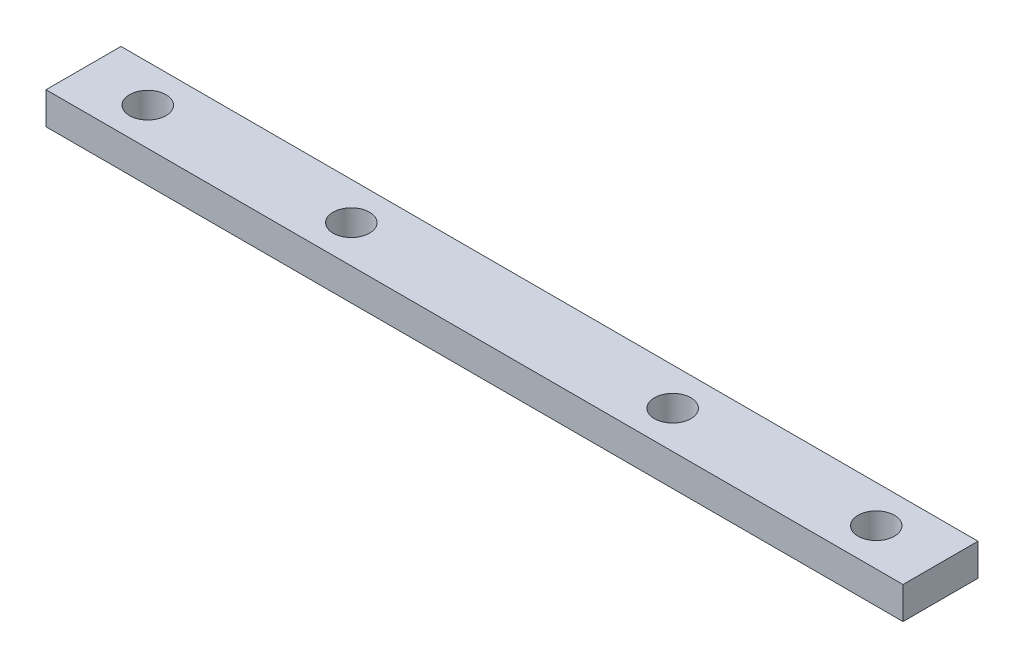
SolidWorks part; units mm, degrees
ref_plane "Front Plane" through (0, 0, 0) normal (0, 0, 1) x (1, 0, 0)
ref_plane "Top Plane" through (0, 0, 0) normal (0, 1, 0) x (1, 0, 0)
ref_plane "Right Plane" through (0, 0, 0) normal (1, 0, 0) x (0, 0, -1)
sketch "Sketch1" plane through (0, 0, 0) normal (0, 1, 0) x (1, 0, 0)
  line L1 (-40, -3.5) -> (40, -3.5)
  line L2 (-40, -3.5) -> (-40, 3.5)
  line L3 (-40, 3.5) -> (40, 3.5)
  line L4 (40, -3.5) -> (40, 3.5)
  line L5 (-40, -3.5) -> (40, 3.5) construction
  line L6 (-40, 3.5) -> (40, -3.5) construction
  point P0 (0, 0)
  dimension "D1" = 80
  dimension "D2" = 7
extrude "Boss-Extrude1" add sketch "Sketch1" along normal blind 3
sketch "Sketch2" plane through (0, 3, 0) normal (0, 1, 0) x (1, 0, 0)
  line L0 (-34, 0) -> (34, 0) construction
  line L3 (-15, 0) -> (15, 0) construction
  line L4 (-40, 3.5) -> (-40, -3.5) construction
  circle A0 centre (-34, 0) radius 1.7
  circle A1 centre (-15, 0) radius 1.7
  circle A2 centre (15, 0) radius 1.7
  circle A3 centre (34, 0) radius 1.7
  point P3 (0, 0)
  point P9 (0, 0)
  point P12 (0, 0)
  dimension "D3" = 3.4
  dimension "D1" = 30
  dimension "D2" = 6
extrude "Cut-Extrude1" cut sketch "Sketch2" against normal through all
